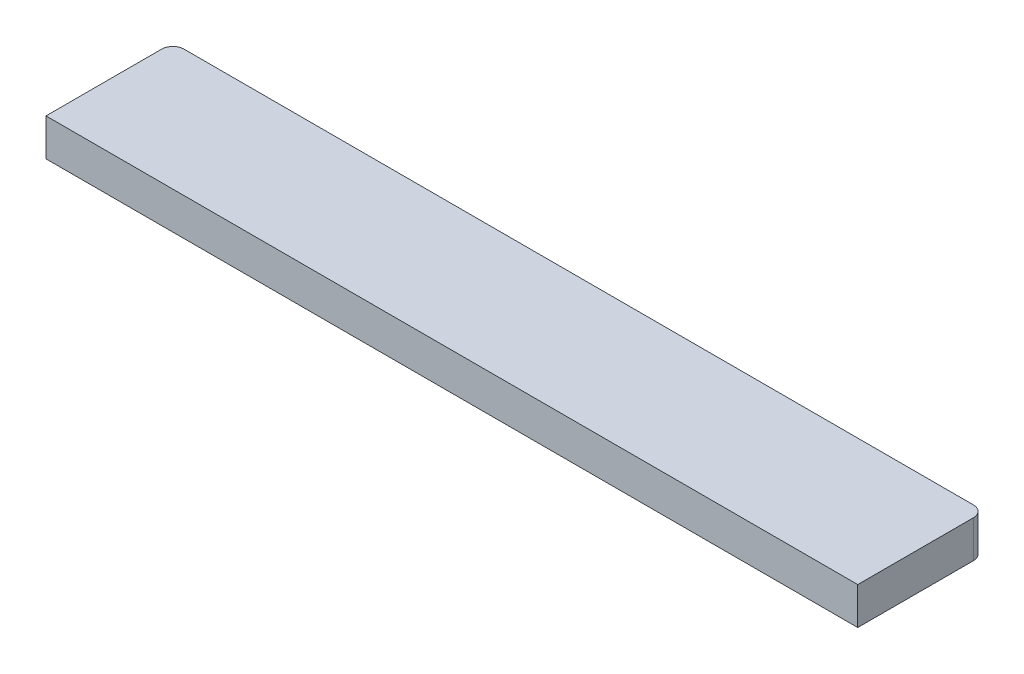
SolidWorks part; units mm, degrees
ref_plane "前视基准面" through (0, 0, 0) normal (0, 0, 1) x (1, 0, 0)
ref_plane "上视基准面" through (0, 0, 0) normal (0, 1, 0) x (1, 0, 0)
ref_plane "右视基准面" through (0, 0, 0) normal (1, 0, 0) x (0, 0, -1)
sketch "草图1" plane through (0, 0, 0) normal (0, 1, 0) x (1, 0, 0)
  line L1 (0, 0) -> (218, 0)
  line L2 (0, 0) -> (0, -34.06)
  line L3 (0, -34.06) -> (218, -34.06)
  line L4 (218, 0) -> (218, -34.06)
  dimension "D1" = 218
  dimension "D2" = 34.06
extrude "凸台-拉伸1" add sketch "草图1" along normal blind 10
fillet "圆角1" radius 3 2 edges at (0, 5, 0) (218, 5, 0)
